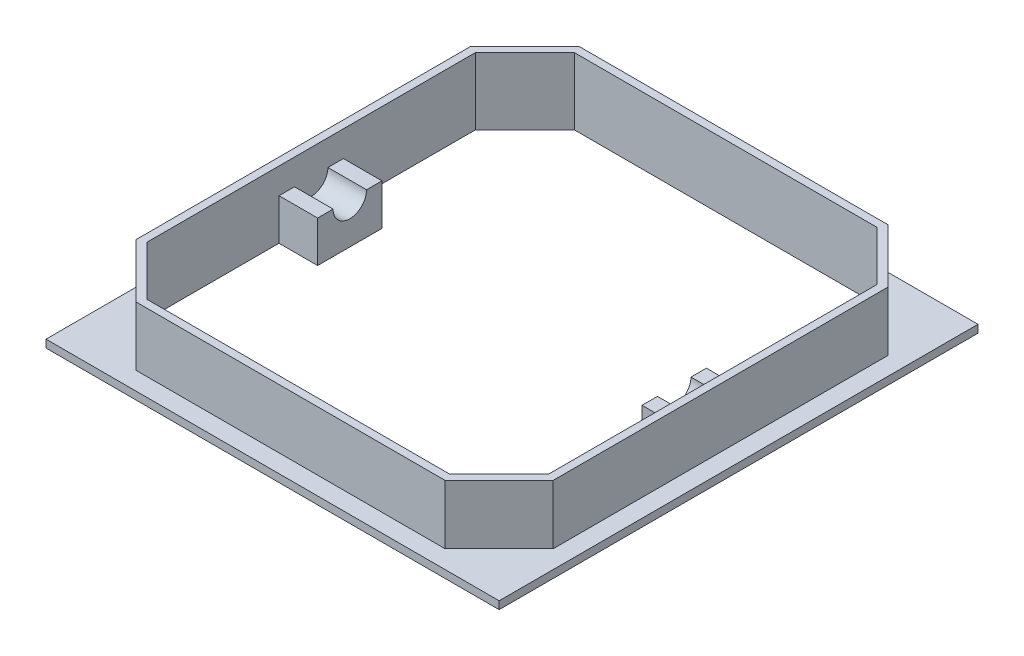
SolidWorks part; units mm, degrees
ref_plane "Front Plane" through (0, 0, 0) normal (0, 0, 1) x (1, 0, 0)
ref_plane "Top Plane" through (0, 0, 0) normal (0, 1, 0) x (1, 0, 0)
ref_plane "Right Plane" through (0, 0, 0) normal (1, 0, 0) x (0, 0, -1)
sketch "Sketch1" plane through (0, 0, 0) normal (0, 1, 0) x (1, 0, 0)
  line L5 (-44, -46.5) -> (44, -46.5)
  line L6 (-44, -46.5) -> (-44, 46.5)
  line L7 (-44, 46.5) -> (44, 46.5)
  line L8 (44, -46.5) -> (44, 46.5)
  line L9 (-44, -46.5) -> (44, 46.5) construction
  line L10 (-44, 46.5) -> (44, -46.5) construction
  point P0 (0, 0)
  dimension "D1" = 88
  dimension "D2" = 93
extrude "Boss-Extrude1" add sketch "Sketch1" along normal blind 13
sketch "Sketch2" plane through (0, 13, 0) normal (0, 1, 0) x (1, 0, 0)
  line L0 (0, 46.5) -> (0, -46.5) construction
  line L1 (-44, -46.5) -> (44, -46.5) construction
  line L2 (-44, 0) -> (44, 0) construction
  line L3 (44, -46.5) -> (44, 46.5) construction
  line L4 (-30, -43) -> (-40.5, -32.5)
  line L5 (-44, 46.5) -> (-44, -46.5) construction
  line L6 (-44, -36.5) -> (-44, -46.5)
  line L7 (-44, -46.5) -> (-34, -46.5)
  line L11 (-30, -43) -> (30, -43)
  line L14 (-34, -46.5) -> (34, -46.5)
  line L15 (-40.5, -32.5) -> (-40.5, 32.5)
  line L17 (-44, -36.5) -> (-44, 36.5)
  line L18 (44, -36.5) -> (44, 36.5)
  line L19 (40.5, -32.5) -> (40.5, 32.5)
  line L20 (44, -46.5) -> (34, -46.5)
  line L21 (44, -36.5) -> (44, -46.5)
  line L22 (30, -43) -> (40.5, -32.5)
  line L23 (30, 43) -> (40.5, 32.5)
  line L24 (44, 36.5) -> (44, 46.5)
  line L25 (44, 46.5) -> (34, 46.5)
  line L26 (-34, 46.5) -> (34, 46.5)
  line L27 (-30, 43) -> (30, 43)
  line L28 (-44, 46.5) -> (-34, 46.5)
  line L29 (-44, 36.5) -> (-44, 46.5)
  line L30 (-30, 43) -> (-40.5, 32.5)
  point P6 (0, 0)
  point P12 (0, 0)
  point P21 (-39.5, -36.5)
  point P22 (-39.5, -37.1194)
  point P29 (0, -43)
  point P35 (40.5, 0)
  point P37 (-40.5, 0)
  point P40 (0, 43)
  point P41 (-38, -33.7481)
  dimension "D1" = 45
  dimension "D2" = 10
  dimension "D3" = 10
  dimension "D4" = 3.5
  dimension "D5" = 3.5
  dimension "D6" = 14
extrude "Cut-Extrude1" cut sketch "Sketch2" against normal offset from surface (11.5 mm away) 1.5 up to face at (0, 0, 0)
sketch "Sketch3" plane through (0, 13, 0) normal (0, 1, 0) x (1, 0, 0)
  line L8 (-29.3787, -41.5) -> (29.3787, -41.5)
  line L9 (29.3787, -41.5) -> (39, -31.8787)
  line L10 (39, -31.8787) -> (39, 31.8787)
  line L11 (39, 31.8787) -> (29.3787, 41.5)
  line L12 (29.3787, 41.5) -> (-29.3787, 41.5)
  line L13 (-29.3787, 41.5) -> (-39, 31.8787)
  line L14 (-39, 31.8787) -> (-39, -31.8787)
  line L15 (-39, -31.8787) -> (-29.3787, -41.5)
  line L16 (36.6167, -41.5) -> (15, -41.5) construction
  line L17 (15, 41.5) -> (36.6167, 41.5) construction
  line L18 (40.5, -32.5) -> (40.5, 32.5) construction
  line L19 (-40.5, 32.5) -> (-40.5, -32.5) construction
  line L20 (-40.5, -32.5) -> (-30, -43) construction
  line L21 (-30, 43) -> (-40.5, 32.5) construction
  line L22 (30, -43) -> (40.5, -32.5) construction
  line L23 (40.5, 32.5) -> (30, 43) construction
  point P24 (-33.7875, 41.5)
  point P25 (38, -35.2789)
  point P26 (33.7875, -41.5)
  point P27 (38, 37.2875)
  point P28 (-38, -37.2875)
  point P29 (38, -37.3157)
  dimension "D1" = 1.5
  dimension "D2" = 1.5
  dimension "D3" = 1.5
extrude "Cut-Extrude2" cut sketch "Sketch3" against normal through all
sketch "Sketch5" plane through (-39, 0, 0) normal (1, 0, 0) x (0, 0, -1)
  line L0 (0, 0) -> (0, 8) construction
  line L1 (31.8787, 0) -> (-31.8787, 0) construction
  line L2 (-6.25, 0) -> (6.25, 0)
  line L3 (-31.8787, 8) -> (31.8787, 8) construction
  line L6 (6.25, 0) -> (6.25, 8)
  line L7 (6.25, 8) -> (3.25, 8)
  line L8 (-6.25, 8) -> (-3.25, 8)
  line L9 (-6.25, 0) -> (-6.25, 8)
  arc A0 (-3.25, 8) -> (3.25, 8) centre (0, 8) ccw
  point P8 (0, 0)
  point P16 (0, 0)
  dimension "D1" = 6.5
  dimension "D2" = 3
  dimension "D3" = 8
extrude "Boss-Extrude2" add sketch "Sketch5" along normal blind 7.5
mirror "Mirror1" about plane through (0, 0, 0) normal (1, 0, 0) of "Boss-Extrude2"
